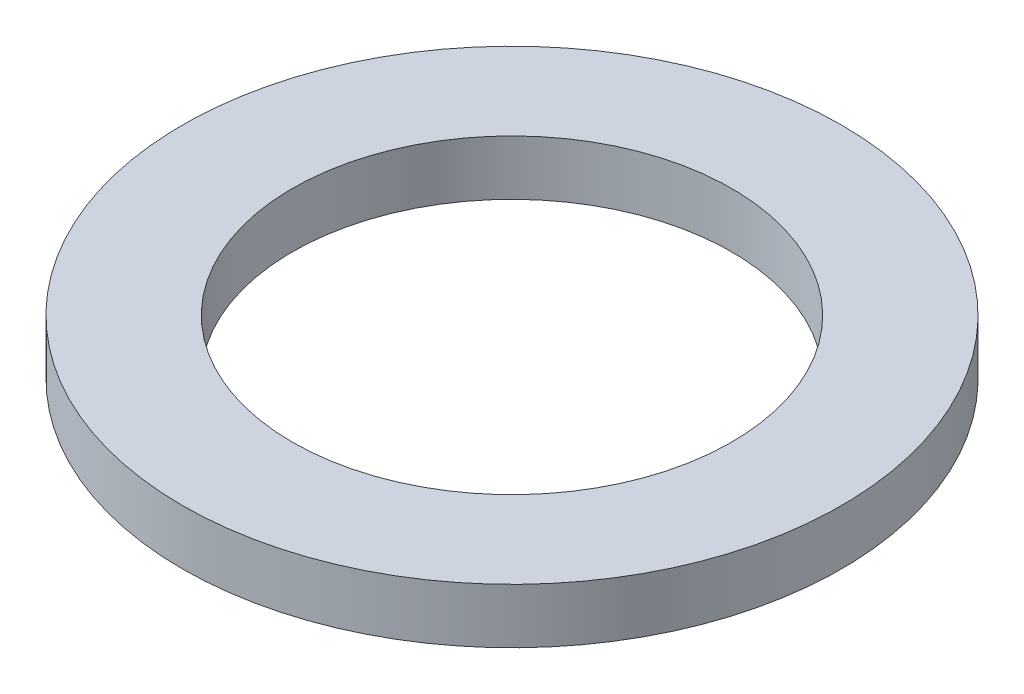
SolidWorks part; units mm, degrees
ref_plane "Front Plane" through (0, 0, 0) normal (0, 0, 1) x (1, 0, 0)
ref_plane "Top Plane" through (0, 0, 0) normal (0, 1, 0) x (1, 0, 0)
ref_plane "Right Plane" through (0, 0, 0) normal (1, 0, 0) x (0, 0, -1)
sketch "Sketch1" plane through (0, 0, 0) normal (0, 1, 0) x (1, 0, 0)
  circle A0 centre (0, 0) radius 30
  circle A1 centre (0, 0) radius 20
  dimension "D1" = 40
  dimension "D2" = 60
extrude "Boss-Extrude1" add sketch "Sketch1" along normal blind 5
